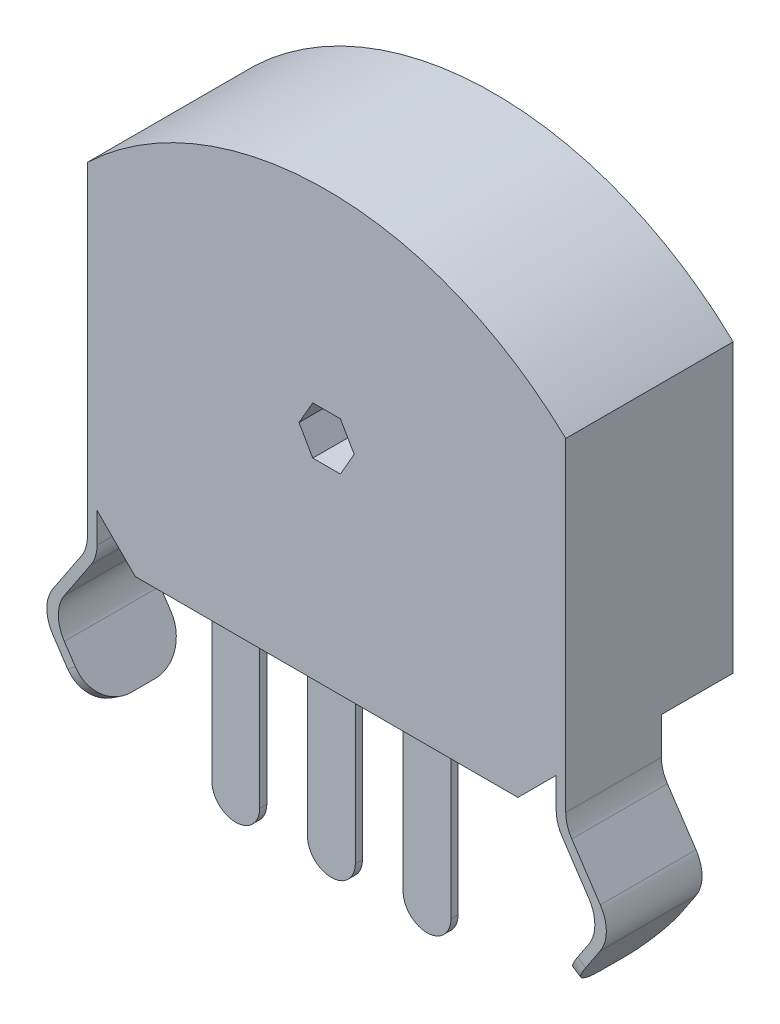
SolidWorks part; units mm, degrees
ref_plane "Plan de face" through (0, 0, 0) normal (0, 0, 1) x (1, 0, 0)
ref_plane "Plan de dessus" through (0, 0, 0) normal (0, 1, 0) x (1, 0, 0)
ref_plane "Plan de droite" through (0, 0, 0) normal (1, 0, 0) x (0, 0, -1)
sketch "Esquisse1" plane through (0, 0, 0) normal (0, 0, 1) x (1, 0, 0)
  line L0 (0, 0) -> (0, 5.4199) construction
  line L1 (-0.2887, 0.5) -> (-0.5774, 0)
  line L2 (-0.5774, 0) -> (-0.2887, -0.5)
  line L3 (-0.2887, -0.5) -> (0.2887, -0.5)
  line L4 (0.2887, -0.5) -> (0.5774, 0)
  line L5 (0.5774, 0) -> (0.2887, 0.5)
  line L6 (0.2887, 0.5) -> (-0.2887, 0.5)
  line L7 (-5, 2.5) -> (-5, -4.5)
  line L8 (-5, -4.5) -> (5, -4.5)
  line L9 (5, 2.5) -> (5, -4.5)
  circle A0 centre (0, 0) radius 0.5 construction
  arc A1 (-5, 2.5) -> (0, 4.5) centre (0, -2.75) cw
  arc A2 (5, 2.5) -> (0, 4.5) centre (0, -2.75) ccw
  point P16 (0, -4.5)
  point P18 (-5, 2.7947)
  dimension "D1" = 1
  dimension "D2" = 10
  dimension "D3" = 9
  dimension "D4" = 4
  dimension "D5" = 7
extrude "Boss.-Extru.1" add sketch "Esquisse1" along normal blind 3.5
sketch "Esquisse2" plane through (0, 0, 0) normal (0, 0, 1) x (1, 0, 0)
  line L1 (-0.5774, 0) -> (-0.2887, -0.5) construction
  line L2 (-0.5774, 0) -> (-0.2887, -0.5)
  line L9 (0.5774, 0) -> (0.2887, 0.5)
  line L10 (0.2887, 0.5) -> (-0.2887, 0.5)
  line L11 (-0.2887, 0.5) -> (-0.5774, 0)
  line L12 (-0.5774, 0) -> (-0.2887, -0.5)
  line L13 (-0.2887, -0.5) -> (0.2887, -0.5)
  line L14 (0.2887, -0.5) -> (0.5774, 0)
  line L15 (0.5774, 0) -> (0.2887, 0.5)
  line L16 (0.2887, 0.5) -> (-0.2887, 0.5)
  line L17 (-0.2887, 0.5) -> (-0.5774, 0)
  line L18 (-0.5774, 0) -> (-0.2887, -0.5)
  line L19 (-0.2887, -0.5) -> (0.2887, -0.5)
  line L20 (0.2887, -0.5) -> (0.5774, 0)
  circle A0 centre (0, 0) radius 1.75
  dimension "D1" = 3.5
  dimension "D2" = 0
extrude "Boss.-Extru.2" add sketch "Esquisse2" against normal blind 0.5 contours A0
fillet "Congé1" radius 0.25 1 edges at (1.75, 0, 0)
sketch "Esquisse3" plane through (0, 0, 3.5) normal (0, 0, 1) x (1, 0, 0)
  line L0 (-0.5, -4.5) -> (-0.5, -7.5)
  line L1 (-5, -4.5) -> (5, -4.5) construction
  line L2 (0, 0) -> (0, -4.5) construction
  line L3 (0.5, -4.5) -> (0.5, -7.5)
  line L4 (-0.5, -4.5) -> (0.5, -4.5)
  arc A0 (-0.5, -7.5) -> (0.5, -7.5) centre (0, -7.5) ccw
  point P10 (0, -8)
  dimension "D1" = 0.5
  dimension "D2" = 3.5
extrude "Boss.-Extru.3" add sketch "Esquisse3" against normal blind 0.15 from offset 0.1 offset against normal yes
pattern_linear "Répétition linéaire1" count 2 spacing 2 along (1, 0, 0) count 2 spacing 2 along (-1, 0, 0) of "Boss.-Extru.3"
chamfer "Chanfrein1" distance 1 angle 45 2 edges at (5, -4.5, 1.75) (-5, -4.5, 1.75)
sketch "Esquisse4" plane through (0, 0, 3.5) normal (0, 0, 1) x (1, 0, 0)
  line L0 (-5, -3.5) -> (-5, -4.5)
  line L1 (-5, -4.5) -> (-6, -6)
  line L2 (-6, -6) -> (-5, -7.5)
  line L3 (-4, -4.5) -> (4, -4.5) construction
  line L4 (-2, -8) -> (-4.5408, -8) construction
  arc A1 (-2.5, -7.5) -> (-1.5, -7.5) centre (-2, -7.5) ccw construction
  dimension "D1" = 0.5
  dimension "D3" = 1
extrude "Extru.-Mince1" add sketch "Esquisse4" against normal blind 2 thin contours L0 L1 L2 thin type one direction reverse wall 0.2
ref_plane "Plan1" through (0, 0, 0) normal (-1, 0, 0) x (0, 0, 1)
mirror "Symétrie1" about plane through (0, 0, 0) normal (-1, 0, 0) of "Extru.-Mince1"
fillet "Congé2" radius 0.75 4 edges at (-4.9168, -7.4445, 3.5) (-4.9168, -7.4445, 1.5) (4.9168, -7.4445, 1.5) (4.9168, -7.4445, 3.5)
fillet "Congé3" radius 0.75 8 edges at (4.8, -4.5606, 2.5) (-4.8, -4.5606, 2.5) (-5.7596, -6, 2.5) (-5, -4.5, 2.5) (-6, -6, 2.5) (5.7596, -6, 2.5) (6, -6, 2.5) (5, -4.5, 2.5)
